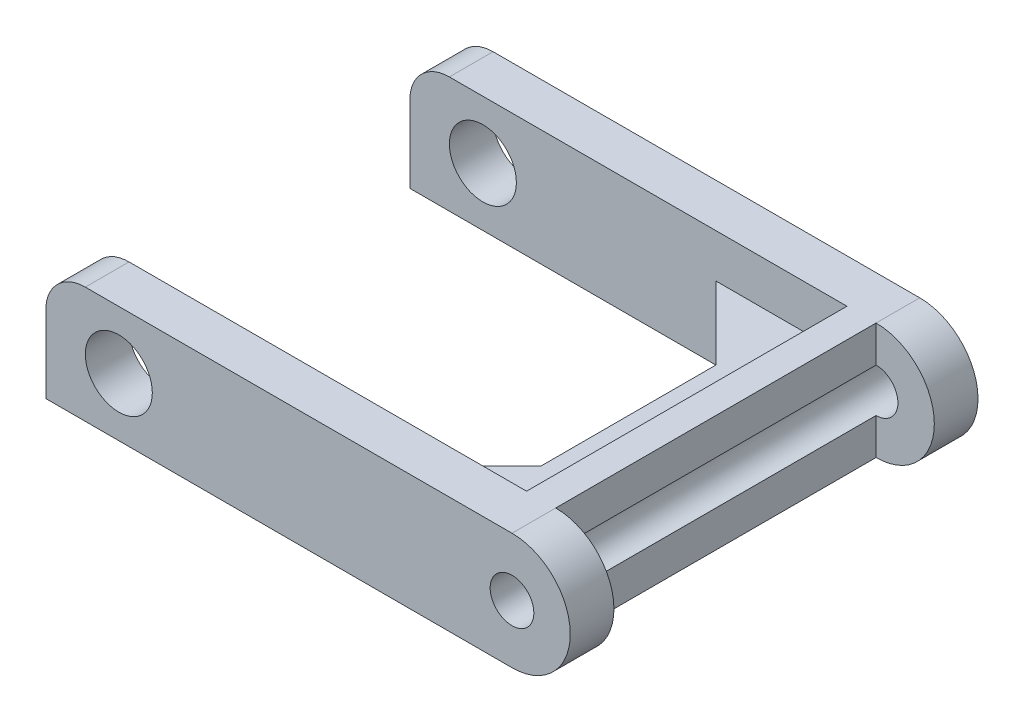
SolidWorks part; units mm, degrees
ref_plane "Front" through (0, 0, 0) normal (0, 0, 1) x (1, 0, 0)
ref_plane "Top" through (0, 0, 0) normal (0, 1, 0) x (1, 0, 0)
ref_plane "Right" through (0, 0, 0) normal (1, 0, 0) x (0, 0, -1)
other "Configuration Table"
sketch "Sketch1" plane through (0, 0, 0) normal (0, 0, 1) x (1, 0, 0)
sketch "Sketch2" plane through (0, 0, 0) normal (0, 0, 1) x (1, 0, 0)
  line L0 (-14.65, 1.9925) -> (0, 2)
  line L1 (-16, 0.5) -> (-16, -2)
  line L2 (-16, -2) -> (0, -2)
  arc A0 (-14.65, 1.9925) -> (-16, 0.5) centre (-14.6493, 0.6351) ccw
  arc A1 (0, -2) -> (0, 2) centre (0, 0) ccw
  circle A2 centre (-13.5, 0) radius 1.15
  circle A3 centre (0, 0) radius 0.75
sketch "Sketch3" plane through (0, 17.5397, 0) normal (0, 1, 0) x (-1, 0, 0)
  line L0 (5.5, -12.5) -> (16, -12.5)
  line L1 (16, -12.5) -> (16, -14)
  line L2 (16, -14) -> (-2, -14)
  line L3 (-2, -14) -> (-2, -12.5)
  line L4 (-2, -12.5) -> (0, -12.5)
  line L5 (0, -12.5) -> (0, -1.5)
  line L6 (0, -1.5) -> (-2, -1.5)
  line L7 (-2, -1.5) -> (-2, 0)
  line L8 (-2, 0) -> (16, 0)
  line L9 (16, 0) -> (16, -1.5)
  line L10 (16, -1.5) -> (5.5, -1.5)
  line L11 (5.5, -1.5) -> (3, -4)
  line L12 (3, -4) -> (3, -10)
  line L13 (3, -10) -> (5.5, -12.5)
  line L14 (5.5, -1.5) -> (1, -1.5)
  line L15 (1, -1.5) -> (1, -12.5)
  line L16 (1, -12.5) -> (5.5, -12.5)
sketch "Sketch4" plane through (-42.9284, 0, 0) normal (-1, 0, 0) x (0, 0, 1)
  line L0 (-10, -0.5) -> (-10, 0.5)
  line L1 (-10, 0.5) -> (-12.5, 0.5)
  line L2 (-12.5, -0.5) -> (-10, -0.5)
  line L3 (-4, -0.5) -> (-4, 0.5)
  line L4 (-1.5, 0.5) -> (-4, 0.5)
  line L5 (-4, -0.5) -> (-1.5, -0.5)
  line L6 (-4, 0.5) -> (-10, 0.5)
  line L7 (-10, -0.5) -> (-4, -0.5)
  line L8 (-12.5, 2) -> (-1.5, 2)
  line L9 (-14, 2) -> (-12.5, 2)
  line L10 (-12.5, 2) -> (-12.5, -2)
  line L11 (-12.5, -2) -> (-14, -2)
  line L12 (-14, -2) -> (-14, 2)
  line L13 (0, -2) -> (-1.5, -2)
  line L14 (-1.5, -2) -> (-1.5, 2)
  line L15 (-1.5, 2) -> (0, 2)
  line L16 (0, 2) -> (0, -2)
sketch "Sketch5" plane through (0, 0, 0) normal (0, 0, 1) x (1, 0, 0)
  line L0 (-14.65, 1.9925) -> (0, 2)
  line L1 (-16, 0.5) -> (-16, -2)
  line L2 (-16, -2) -> (0, -2)
  arc A0 (-14.65, 1.9925) -> (-16, 0.5) centre (-14.6493, 0.6351) ccw
  arc A1 (0, -2) -> (0, 2) centre (0, 0) ccw
  circle A2 centre (-13.5, 0) radius 1.15
  circle A3 centre (0, 0) radius 0.75
extrude "Base-Extrude" add sketch "Sketch5" against normal blind 14
sketch "Sketch7" plane through (0, 17.5397, 0) normal (0, 1, 0) x (-1, 0, 0)
  line L0 (5.5, -12.5) -> (16, -12.5)
  line L1 (16, -12.5) -> (16, -14)
  line L2 (16, -14) -> (-2, -14)
  line L3 (-2, -14) -> (-2, -12.5)
  line L4 (-2, -12.5) -> (0, -12.5)
  line L5 (0, -12.5) -> (0, -1.5)
  line L6 (0, -1.5) -> (-2, -1.5)
  line L7 (-2, -1.5) -> (-2, 0)
  line L8 (-2, 0) -> (16, 0)
  line L9 (16, 0) -> (16, -1.5)
  line L10 (16, -1.5) -> (5.5, -1.5)
  line L11 (5.5, -1.5) -> (1, -1.5)
  line L12 (1, -1.5) -> (1, -12.5)
  line L13 (1, -12.5) -> (5.5, -12.5)
sketch "Sketch9" plane through (0, 17.5397, 0) normal (0, 1, 0) x (-1, 0, 0)
  line L0 (5.5, -12.5) -> (16, -12.5)
  line L1 (16, -12.5) -> (16, -14)
  line L2 (16, -14) -> (-2, -14)
  line L3 (-2, -14) -> (-2, -12.5)
  line L4 (-2, -12.5) -> (0, -12.5)
  line L5 (0, -12.5) -> (0, -1.5)
  line L6 (0, -1.5) -> (-2, -1.5)
  line L7 (-2, -1.5) -> (-2, 0)
  line L8 (-2, 0) -> (16, 0)
  line L9 (16, 0) -> (16, -1.5)
  line L10 (16, -1.5) -> (5.5, -1.5)
  line L11 (5.5, -1.5) -> (1, -1.5)
  line L12 (1, -1.5) -> (1, -12.5)
  line L13 (1, -12.5) -> (5.5, -12.5)
extrude "Cut-Extrude2" cut sketch "Sketch9" against normal blind 37 flip side to cut
sketch "Sketch10" plane through (-42.9284, 0.5, -4) normal (0, 1, 0) x (-1, 0, 0)
  line L0 (-37.4284, 2.5) -> (-39.9284, 0)
  line L1 (-39.9284, 0) -> (-39.9284, -6)
  line L2 (-39.9284, -6) -> (-37.4284, -8.5)
  line L3 (-37.4284, 2.5) -> (-41.9284, 2.5)
  line L4 (-41.9284, 2.5) -> (-41.9284, -8.5)
  line L5 (-41.9284, -8.5) -> (-37.4284, -8.5)
extrude "Boss-Extrude1" add sketch "Sketch10" against normal blind 1
